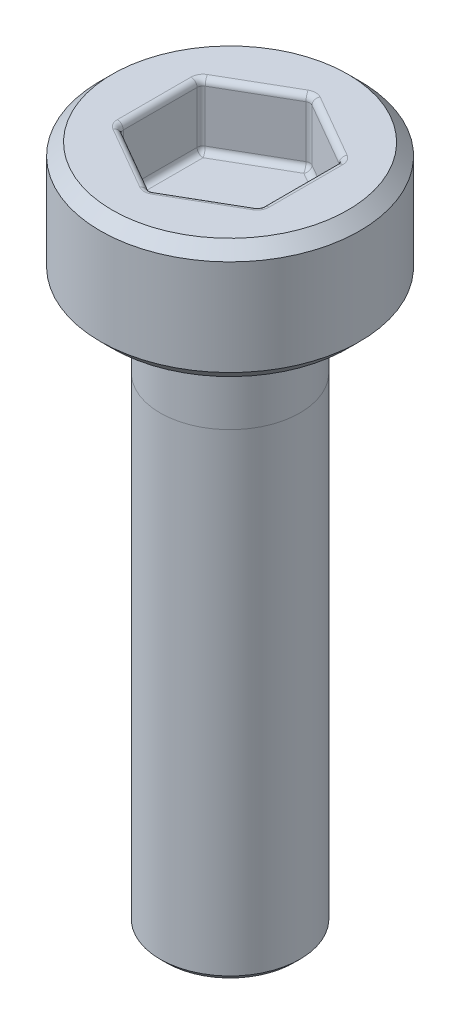
SolidWorks part; units mm, degrees
ref_plane "Front Plane" through (0, 0, 0) normal (0, 0, 1) x (1, 0, 0)
ref_plane "Top Plane" through (0, 0, 0) normal (0, 1, 0) x (1, 0, 0)
ref_plane "Right Plane" through (0, 0, 0) normal (1, 0, 0) x (0, 0, -1)
sketch "Sketch1" plane through (0, 0, 0) normal (0, 1, 0) x (1, 0, 0)
  circle A0 centre (0, 0) radius 0.875
  dimension "D1" = 1.75
extrude "Boss-Extrude1" add sketch "Sketch1" along normal blind 7
sketch "Sketch2" plane through (0, 7, 0) normal (0, 1, 0) x (1, 0, 0)
  circle A0 centre (0, 0) radius 1.625
  dimension "D1" = 3.25
extrude "Boss-Extrude2" add sketch "Sketch2" along normal blind 1.5
fillet "Fillet1" radius 0.15 1 edges at (0, 7, 0.875)
chamfer "Chamfer1" distance 0.15 angle 45 2 edges at (0, 8.5, 1.625) (0, 7, 1.625)
sketch "Sketch3" plane through (0, 8.5, 0) normal (0, 1, 0) x (1, 0, 0)
  line L1 (0, 1.0104) -> (-0.875, 0.5052)
  line L2 (-0.875, 0.5052) -> (-0.875, -0.5052)
  line L3 (-0.875, -0.5052) -> (0, -1.0104)
  line L4 (0, -1.0104) -> (0.875, -0.5052)
  line L5 (0.875, -0.5052) -> (0.875, 0.5052)
  line L6 (0.875, 0.5052) -> (0, 1.0104)
  circle A0 centre (0, 0) radius 0.875 construction
  dimension "D1" = 1.75
extrude "Cut-Extrude1" cut sketch "Sketch3" against normal blind 0.8
chamfer "Chamfer2" distance 0.075 angle 45 1 edges at (0, 0, 0.875)
fillet "Fillet2" radius 0.075 18 edges at (0.4375, 8.5, -0.7578) (-0.4375, 8.5, -0.7578) (-0.875, 8.5, 0) (-0.4375, 8.5, 0.7578) (0.4375, 8.5, 0.7578) (0.875, 8.5, 0) (-0.4375, 7.7, -0.7578) (-0.875, 7.7, 0) (-0.4375, 7.7, 0.7578) (0.4375, 7.7, 0.7578) (0.875, 7.7, 0) (0, 8.1, -1.0104) (-0.875, 8.1, -0.5052) (-0.875, 8.1, 0.5052) (0, 8.1, 1.0104) (0.875, 8.1, 0.5052) (0.875, 8.1, -0.5052) (0.4375, 7.7, -0.7578)
sketch "Sketch4" plane through (0, 0, 0) normal (0, 0, 1) x (1, 0, 0)
  line L0 (-5.6741, 6) -> (6.8738, 6)
  dimension "D1" = 6
split line "Split Line1"
